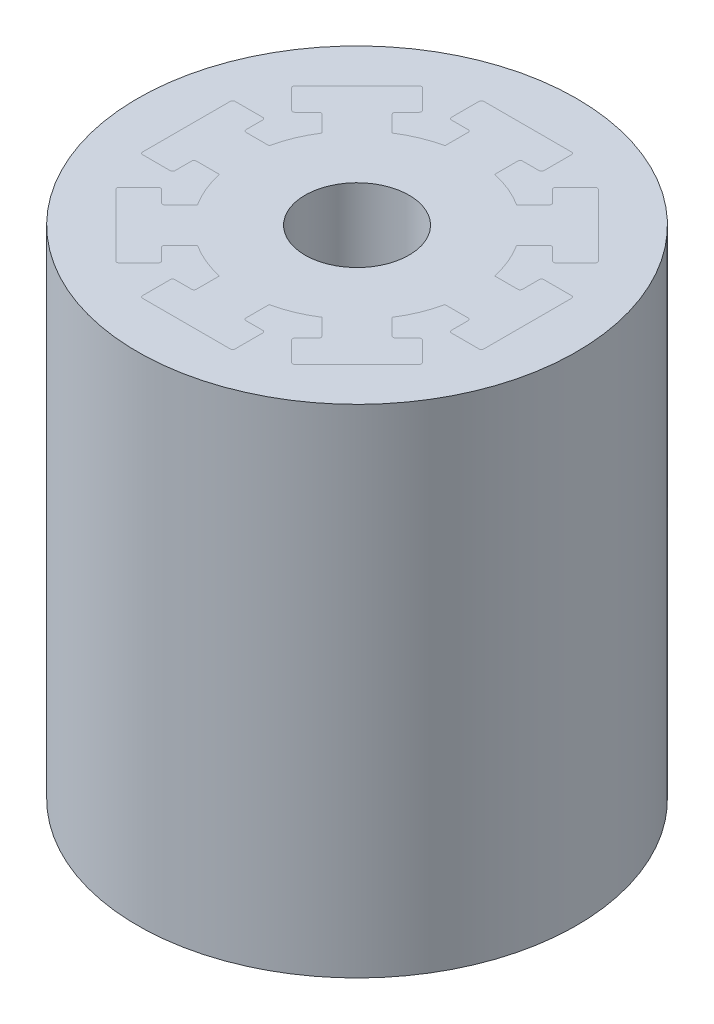
SolidWorks part; units mm, degrees
ref_plane "Front Plane" through (0, 0, 0) normal (0, 0, 1) x (1, 0, 0)
ref_plane "Top Plane" through (0, 0, 0) normal (0, 1, 0) x (1, 0, 0)
ref_plane "Right Plane" through (0, 0, 0) normal (1, 0, 0) x (0, 0, -1)
sketch "Sketch1" plane through (0, 0, 0) normal (0, 1, 0) x (1, 0, 0)
  line L0 (-2.15, 11.7661) -> (-2.15, 9.7661)
  line L1 (-2.35, 11.9661) -> (-3.8, 11.9661)
  line L2 (-4, 12.1661) -> (-4, 14.5661)
  line L3 (-3.8, 14.7661) -> (3.8, 14.7661)
  line L4 (0, 10) -> (0, 14.7661) construction
  line L5 (2.15, 11.7661) -> (2.15, 9.7661)
  line L6 (2.35, 11.9661) -> (3.8, 11.9661)
  line L7 (4, 12.1661) -> (4, 14.5661)
  line L8 (7.7542, 13.1282) -> (13.1282, 7.7542)
  line L9 (11.4312, 5.7743) -> (13.1282, 7.4714)
  line L10 (10.123, 6.7996) -> (11.1483, 5.7743)
  line L11 (9.8402, 6.7996) -> (8.426, 5.3854)
  line L12 (6.7996, 9.8402) -> (5.3854, 8.426)
  line L13 (6.7996, 10.123) -> (5.7743, 11.1483)
  line L14 (5.7743, 11.4312) -> (7.4714, 13.1282)
  line L15 (14.7661, 3.8) -> (14.7661, -3.8)
  line L16 (12.1661, -4) -> (14.5661, -4)
  line L17 (11.9661, -2.35) -> (11.9661, -3.8)
  line L18 (11.7661, -2.15) -> (9.7661, -2.15)
  line L19 (11.7661, 2.15) -> (9.7661, 2.15)
  line L20 (11.9661, 2.35) -> (11.9661, 3.8)
  line L21 (12.1661, 4) -> (14.5661, 4)
  line L22 (13.1282, -7.7542) -> (7.7542, -13.1282)
  line L23 (5.7743, -11.4312) -> (7.4714, -13.1282)
  line L24 (6.7996, -10.123) -> (5.7743, -11.1483)
  line L25 (6.7996, -9.8402) -> (5.3854, -8.426)
  line L26 (9.8402, -6.7996) -> (8.426, -5.3854)
  line L27 (10.123, -6.7996) -> (11.1483, -5.7743)
  line L28 (11.4312, -5.7743) -> (13.1282, -7.4714)
  line L29 (3.8, -14.7661) -> (-3.8, -14.7661)
  line L30 (-4, -12.1661) -> (-4, -14.5661)
  line L31 (-2.35, -11.9661) -> (-3.8, -11.9661)
  line L32 (-2.15, -11.7661) -> (-2.15, -9.7661)
  line L33 (2.15, -11.7661) -> (2.15, -9.7661)
  line L34 (2.35, -11.9661) -> (3.8, -11.9661)
  line L35 (4, -12.1661) -> (4, -14.5661)
  line L36 (-7.7542, -13.1282) -> (-13.1282, -7.7542)
  line L37 (-11.4312, -5.7743) -> (-13.1282, -7.4714)
  line L38 (-10.123, -6.7996) -> (-11.1483, -5.7743)
  line L39 (-9.8402, -6.7996) -> (-8.426, -5.3854)
  line L40 (-6.7996, -9.8402) -> (-5.3854, -8.426)
  line L41 (-6.7996, -10.123) -> (-5.7743, -11.1483)
  line L42 (-5.7743, -11.4312) -> (-7.4714, -13.1282)
  line L43 (-14.7661, -3.8) -> (-14.7661, 3.8)
  line L44 (-12.1661, 4) -> (-14.5661, 4)
  line L45 (-11.9661, 2.35) -> (-11.9661, 3.8)
  line L46 (-11.7661, 2.15) -> (-9.7661, 2.15)
  line L47 (-11.7661, -2.15) -> (-9.7661, -2.15)
  line L48 (-11.9661, -2.35) -> (-11.9661, -3.8)
  line L49 (-12.1661, -4) -> (-14.5661, -4)
  line L50 (-13.1282, 7.7542) -> (-7.7542, 13.1282)
  line L51 (-5.7743, 11.4312) -> (-7.4714, 13.1282)
  line L52 (-6.7996, 10.123) -> (-5.7743, 11.1483)
  line L53 (-6.7996, 9.8402) -> (-5.3854, 8.426)
  line L54 (-9.8402, 6.7996) -> (-8.426, 5.3854)
  line L55 (-10.123, 6.7996) -> (-11.1483, 5.7743)
  line L56 (-11.4312, 5.7743) -> (-13.1282, 7.4714)
  arc A0 (-2.15, 9.7661) -> (-5.3854, 8.426) centre (0, 0) ccw
  arc A1 (-2.15, 11.7661) -> (-2.35, 11.9661) centre (-2.35, 11.7661) ccw
  arc A2 (-3.8, 11.9661) -> (-4, 12.1661) centre (-3.8, 12.1661) cw
  arc A3 (-4, 14.5661) -> (-3.8, 14.7661) centre (-3.8, 14.5661) cw
  arc A4 (2.15, 11.7661) -> (2.35, 11.9661) centre (2.35, 11.7661) cw
  arc A5 (3.8, 11.9661) -> (4, 12.1661) centre (3.8, 12.1661) ccw
  arc A6 (4, 14.5661) -> (3.8, 14.7661) centre (3.8, 14.5661) ccw
  arc A7 (13.1282, 7.4714) -> (13.1282, 7.7542) centre (12.9868, 7.6128) ccw
  arc A8 (11.1483, 5.7743) -> (11.4312, 5.7743) centre (11.2898, 5.9158) ccw
  arc A9 (9.8402, 6.7996) -> (10.123, 6.7996) centre (9.9816, 6.6582) cw
  arc A10 (6.7996, 9.8402) -> (6.7996, 10.123) centre (6.6582, 9.9816) ccw
  arc A11 (5.7743, 11.1483) -> (5.7743, 11.4312) centre (5.9158, 11.2898) cw
  arc A12 (7.4714, 13.1282) -> (7.7542, 13.1282) centre (7.6128, 12.9868) cw
  arc A13 (14.5661, -4) -> (14.7661, -3.8) centre (14.5661, -3.8) ccw
  arc A14 (11.9661, -3.8) -> (12.1661, -4) centre (12.1661, -3.8) ccw
  arc A15 (11.7661, -2.15) -> (11.9661, -2.35) centre (11.7661, -2.35) cw
  arc A16 (11.7661, 2.15) -> (11.9661, 2.35) centre (11.7661, 2.35) ccw
  arc A17 (11.9661, 3.8) -> (12.1661, 4) centre (12.1661, 3.8) cw
  arc A18 (14.5661, 4) -> (14.7661, 3.8) centre (14.5661, 3.8) cw
  arc A19 (7.4714, -13.1282) -> (7.7542, -13.1282) centre (7.6128, -12.9868) ccw
  arc A20 (5.7743, -11.1483) -> (5.7743, -11.4312) centre (5.9158, -11.2898) ccw
  arc A21 (6.7996, -9.8402) -> (6.7996, -10.123) centre (6.6582, -9.9816) cw
  arc A22 (9.8402, -6.7996) -> (10.123, -6.7996) centre (9.9816, -6.6582) ccw
  arc A23 (11.1483, -5.7743) -> (11.4312, -5.7743) centre (11.2898, -5.9158) cw
  arc A24 (13.1282, -7.4714) -> (13.1282, -7.7542) centre (12.9868, -7.6128) cw
  arc A25 (-4, -14.5661) -> (-3.8, -14.7661) centre (-3.8, -14.5661) ccw
  arc A26 (-3.8, -11.9661) -> (-4, -12.1661) centre (-3.8, -12.1661) ccw
  arc A27 (-2.15, -11.7661) -> (-2.35, -11.9661) centre (-2.35, -11.7661) cw
  arc A28 (2.15, -11.7661) -> (2.35, -11.9661) centre (2.35, -11.7661) ccw
  arc A29 (3.8, -11.9661) -> (4, -12.1661) centre (3.8, -12.1661) cw
  arc A30 (4, -14.5661) -> (3.8, -14.7661) centre (3.8, -14.5661) cw
  arc A31 (-13.1282, -7.4714) -> (-13.1282, -7.7542) centre (-12.9868, -7.6128) ccw
  arc A32 (-11.1483, -5.7743) -> (-11.4312, -5.7743) centre (-11.2898, -5.9158) ccw
  arc A33 (-9.8402, -6.7996) -> (-10.123, -6.7996) centre (-9.9816, -6.6582) cw
  arc A34 (-6.7996, -9.8402) -> (-6.7996, -10.123) centre (-6.6582, -9.9816) ccw
  arc A35 (-5.7743, -11.1483) -> (-5.7743, -11.4312) centre (-5.9158, -11.2898) cw
  arc A36 (-7.4714, -13.1282) -> (-7.7542, -13.1282) centre (-7.6128, -12.9868) cw
  arc A37 (-14.5661, 4) -> (-14.7661, 3.8) centre (-14.5661, 3.8) ccw
  arc A38 (-11.9661, 3.8) -> (-12.1661, 4) centre (-12.1661, 3.8) ccw
  arc A39 (-11.7661, 2.15) -> (-11.9661, 2.35) centre (-11.7661, 2.35) cw
  arc A40 (-11.7661, -2.15) -> (-11.9661, -2.35) centre (-11.7661, -2.35) ccw
  arc A41 (-11.9661, -3.8) -> (-12.1661, -4) centre (-12.1661, -3.8) cw
  arc A42 (-14.5661, -4) -> (-14.7661, -3.8) centre (-14.5661, -3.8) cw
  arc A43 (-7.4714, 13.1282) -> (-7.7542, 13.1282) centre (-7.6128, 12.9868) ccw
  arc A44 (-5.7743, 11.1483) -> (-5.7743, 11.4312) centre (-5.9158, 11.2898) ccw
  arc A45 (-6.7996, 9.8402) -> (-6.7996, 10.123) centre (-6.6582, 9.9816) cw
  arc A46 (-9.8402, 6.7996) -> (-10.123, 6.7996) centre (-9.9816, 6.6582) ccw
  arc A47 (-11.1483, 5.7743) -> (-11.4312, 5.7743) centre (-11.2898, 5.9158) cw
  arc A48 (-13.1282, 7.4714) -> (-13.1282, 7.7542) centre (-12.9868, 7.6128) cw
  arc A49 (5.3854, 8.426) -> (2.15, 9.7661) centre (0, 0) ccw
  arc A50 (9.7661, 2.15) -> (8.426, 5.3854) centre (0, 0) ccw
  arc A51 (8.426, -5.3854) -> (9.7661, -2.15) centre (0, 0) ccw
  arc A52 (2.15, -9.7661) -> (5.3854, -8.426) centre (0, 0) ccw
  arc A53 (-5.3854, -8.426) -> (-2.15, -9.7661) centre (0, 0) ccw
  arc A54 (-9.7661, -2.15) -> (-8.426, -5.3854) centre (0, 0) ccw
  arc A55 (-8.426, 5.3854) -> (-9.7661, 2.15) centre (0, 0) ccw
  circle A56 centre (0, 0) radius 4.5
  point P167 (0, 0)
  dimension "D1" = 20
  dimension "D2" = 5
  dimension "D3" = 0.2
  dimension "D5" = 0.2
  dimension "D4" = 0.2
  dimension "D10" = 9
  dimension "D6" = 2.8
  dimension "D7" = 4.3
  dimension "D8" = 8
  dimension "D9" = 8
extrude "Boss-Extrude1" add sketch "Sketch1" along normal blind 43
sketch "Sketch2" plane through (0, 0, 0) normal (0, -1, 0) x (1, 0, 0)
  line L56 (-2.35, -11.9661) -> (-3.8, -11.9661)
  line L57 (-4, -12.1661) -> (-4, -14.5661)
  line L58 (-3.8, -14.7661) -> (3.8, -14.7661)
  line L59 (4, -14.5661) -> (4, -12.1661)
  line L60 (3.8, -11.9661) -> (2.35, -11.9661)
  line L61 (2.15, -11.7661) -> (2.15, -9.7661)
  line L62 (5.3854, -8.426) -> (6.7996, -9.8402)
  line L63 (6.7996, -10.123) -> (5.7743, -11.1483)
  line L64 (5.7743, -11.4312) -> (7.4714, -13.1282)
  line L65 (7.7542, -13.1282) -> (13.1282, -7.7542)
  line L66 (13.1282, -7.4714) -> (11.4312, -5.7743)
  line L67 (11.1483, -5.7743) -> (10.123, -6.7996)
  line L68 (9.8402, -6.7996) -> (8.426, -5.3854)
  line L69 (9.7661, -2.15) -> (11.7661, -2.15)
  line L70 (11.9661, -2.35) -> (11.9661, -3.8)
  line L71 (12.1661, -4) -> (14.5661, -4)
  line L72 (14.7661, -3.8) -> (14.7661, 3.8)
  line L73 (14.5661, 4) -> (12.1661, 4)
  line L74 (11.9661, 3.8) -> (11.9661, 2.35)
  line L75 (11.7661, 2.15) -> (9.7661, 2.15)
  line L76 (8.426, 5.3854) -> (9.8402, 6.7996)
  line L77 (10.123, 6.7996) -> (11.1483, 5.7743)
  line L78 (11.4312, 5.7743) -> (13.1282, 7.4714)
  line L79 (13.1282, 7.7542) -> (7.7542, 13.1282)
  line L80 (7.4714, 13.1282) -> (5.7743, 11.4312)
  line L81 (5.7743, 11.1483) -> (6.7996, 10.123)
  line L82 (6.7996, 9.8402) -> (5.3854, 8.426)
  line L83 (2.15, 9.7661) -> (2.15, 11.7661)
  line L84 (2.35, 11.9661) -> (3.8, 11.9661)
  line L85 (4, 12.1661) -> (4, 14.5661)
  line L86 (3.8, 14.7661) -> (-3.8, 14.7661)
  line L87 (-4, 14.5661) -> (-4, 12.1661)
  line L88 (-3.8, 11.9661) -> (-2.35, 11.9661)
  line L89 (-2.15, 11.7661) -> (-2.15, 9.7661)
  line L90 (-5.3854, 8.426) -> (-6.7996, 9.8402)
  line L91 (-6.7996, 10.123) -> (-5.7743, 11.1483)
  line L92 (-5.7743, 11.4312) -> (-7.4714, 13.1282)
  line L93 (-7.7542, 13.1282) -> (-13.1282, 7.7542)
  line L94 (-13.1282, 7.4714) -> (-11.4312, 5.7743)
  line L95 (-11.1483, 5.7743) -> (-10.123, 6.7996)
  line L96 (-9.8402, 6.7996) -> (-8.426, 5.3854)
  line L97 (-9.7661, 2.15) -> (-11.7661, 2.15)
  line L98 (-11.9661, 2.35) -> (-11.9661, 3.8)
  line L99 (-12.1661, 4) -> (-14.5661, 4)
  line L100 (-14.7661, 3.8) -> (-14.7661, -3.8)
  line L101 (-14.5661, -4) -> (-12.1661, -4)
  line L102 (-11.9661, -3.8) -> (-11.9661, -2.35)
  line L103 (-11.7661, -2.15) -> (-9.7661, -2.15)
  line L104 (-8.426, -5.3854) -> (-9.8402, -6.7996)
  line L105 (-10.123, -6.7996) -> (-11.1483, -5.7743)
  line L106 (-11.4312, -5.7743) -> (-13.1282, -7.4714)
  line L107 (-13.1282, -7.7542) -> (-7.7542, -13.1282)
  line L108 (-7.4714, -13.1282) -> (-5.7743, -11.4312)
  line L109 (-5.7743, -11.1483) -> (-6.7996, -10.123)
  line L110 (-6.7996, -9.8402) -> (-5.3854, -8.426)
  line L111 (-2.15, -9.7661) -> (-2.15, -11.7661)
  line L112 (-2.35, -11.9661) -> (-3.8, -11.9661)
  line L113 (-4, -12.1661) -> (-4, -14.5661)
  line L114 (-3.8, -14.7661) -> (3.8, -14.7661)
  line L115 (4, -14.5661) -> (4, -12.1661)
  line L116 (3.8, -11.9661) -> (2.35, -11.9661)
  line L117 (2.15, -11.7661) -> (2.15, -9.7661)
  line L118 (5.3854, -8.426) -> (6.7996, -9.8402)
  line L119 (6.7996, -10.123) -> (5.7743, -11.1483)
  line L120 (5.7743, -11.4312) -> (7.4714, -13.1282)
  line L121 (7.7542, -13.1282) -> (13.1282, -7.7542)
  line L122 (13.1282, -7.4714) -> (11.4312, -5.7743)
  line L123 (11.1483, -5.7743) -> (10.123, -6.7996)
  line L124 (9.8402, -6.7996) -> (8.426, -5.3854)
  line L125 (9.7661, -2.15) -> (11.7661, -2.15)
  line L126 (11.9661, -2.35) -> (11.9661, -3.8)
  line L127 (12.1661, -4) -> (14.5661, -4)
  line L128 (14.7661, -3.8) -> (14.7661, 3.8)
  line L129 (14.5661, 4) -> (12.1661, 4)
  line L130 (11.9661, 3.8) -> (11.9661, 2.35)
  line L131 (11.7661, 2.15) -> (9.7661, 2.15)
  line L132 (8.426, 5.3854) -> (9.8402, 6.7996)
  line L133 (10.123, 6.7996) -> (11.1483, 5.7743)
  line L134 (11.4312, 5.7743) -> (13.1282, 7.4714)
  line L135 (13.1282, 7.7542) -> (7.7542, 13.1282)
  line L136 (7.4714, 13.1282) -> (5.7743, 11.4312)
  line L137 (5.7743, 11.1483) -> (6.7996, 10.123)
  line L138 (6.7996, 9.8402) -> (5.3854, 8.426)
  line L139 (2.15, 9.7661) -> (2.15, 11.7661)
  line L140 (2.35, 11.9661) -> (3.8, 11.9661)
  line L141 (4, 12.1661) -> (4, 14.5661)
  line L142 (3.8, 14.7661) -> (-3.8, 14.7661)
  line L143 (-4, 14.5661) -> (-4, 12.1661)
  line L144 (-3.8, 11.9661) -> (-2.35, 11.9661)
  line L145 (-2.15, 11.7661) -> (-2.15, 9.7661)
  line L146 (-5.3854, 8.426) -> (-6.7996, 9.8402)
  line L147 (-6.7996, 10.123) -> (-5.7743, 11.1483)
  line L148 (-5.7743, 11.4312) -> (-7.4714, 13.1282)
  line L149 (-7.7542, 13.1282) -> (-13.1282, 7.7542)
  line L150 (-13.1282, 7.4714) -> (-11.4312, 5.7743)
  line L151 (-11.1483, 5.7743) -> (-10.123, 6.7996)
  line L152 (-9.8402, 6.7996) -> (-8.426, 5.3854)
  line L153 (-9.7661, 2.15) -> (-11.7661, 2.15)
  line L154 (-11.9661, 2.35) -> (-11.9661, 3.8)
  line L155 (-12.1661, 4) -> (-14.5661, 4)
  line L156 (-14.7661, 3.8) -> (-14.7661, -3.8)
  line L157 (-14.5661, -4) -> (-12.1661, -4)
  line L158 (-11.9661, -3.8) -> (-11.9661, -2.35)
  line L159 (-11.7661, -2.15) -> (-9.7661, -2.15)
  line L160 (-8.426, -5.3854) -> (-9.8402, -6.7996)
  line L161 (-10.123, -6.7996) -> (-11.1483, -5.7743)
  line L162 (-11.4312, -5.7743) -> (-13.1282, -7.4714)
  line L163 (-13.1282, -7.7542) -> (-7.7542, -13.1282)
  line L164 (-7.4714, -13.1282) -> (-5.7743, -11.4312)
  line L165 (-5.7743, -11.1483) -> (-6.7996, -10.123)
  line L166 (-6.7996, -9.8402) -> (-5.3854, -8.426)
  line L167 (-2.15, -9.7661) -> (-2.15, -11.7661)
  circle A1 centre (0, 0) radius 19
  arc A57 (-2.35, -11.9661) -> (-2.15, -11.7661) centre (-2.35, -11.7661) ccw
  arc A58 (-3.8, -11.9661) -> (-4, -12.1661) centre (-3.8, -12.1661) ccw
  arc A59 (-4, -14.5661) -> (-3.8, -14.7661) centre (-3.8, -14.5661) ccw
  arc A60 (3.8, -14.7661) -> (4, -14.5661) centre (3.8, -14.5661) ccw
  arc A61 (4, -12.1661) -> (3.8, -11.9661) centre (3.8, -12.1661) ccw
  arc A62 (2.15, -11.7661) -> (2.35, -11.9661) centre (2.35, -11.7661) ccw
  arc A63 (2.15, -9.7661) -> (5.3854, -8.426) centre (0, 0) ccw
  arc A64 (6.7996, -10.123) -> (6.7996, -9.8402) centre (6.6582, -9.9816) ccw
  arc A65 (5.7743, -11.1483) -> (5.7743, -11.4312) centre (5.9158, -11.2898) ccw
  arc A66 (7.4714, -13.1282) -> (7.7542, -13.1282) centre (7.6128, -12.9868) ccw
  arc A67 (13.1282, -7.7542) -> (13.1282, -7.4714) centre (12.9868, -7.6128) ccw
  arc A68 (11.4312, -5.7743) -> (11.1483, -5.7743) centre (11.2898, -5.9158) ccw
  arc A69 (9.8402, -6.7996) -> (10.123, -6.7996) centre (9.9816, -6.6582) ccw
  arc A70 (8.426, -5.3854) -> (9.7661, -2.15) centre (0, 0) ccw
  arc A71 (11.9661, -2.35) -> (11.7661, -2.15) centre (11.7661, -2.35) ccw
  arc A72 (11.9661, -3.8) -> (12.1661, -4) centre (12.1661, -3.8) ccw
  arc A73 (14.5661, -4) -> (14.7661, -3.8) centre (14.5661, -3.8) ccw
  arc A74 (14.7661, 3.8) -> (14.5661, 4) centre (14.5661, 3.8) ccw
  arc A75 (12.1661, 4) -> (11.9661, 3.8) centre (12.1661, 3.8) ccw
  arc A76 (11.7661, 2.15) -> (11.9661, 2.35) centre (11.7661, 2.35) ccw
  arc A77 (9.7661, 2.15) -> (8.426, 5.3854) centre (0, 0) ccw
  arc A78 (10.123, 6.7996) -> (9.8402, 6.7996) centre (9.9816, 6.6582) ccw
  arc A79 (11.1483, 5.7743) -> (11.4312, 5.7743) centre (11.2898, 5.9158) ccw
  arc A80 (13.1282, 7.4714) -> (13.1282, 7.7542) centre (12.9868, 7.6128) ccw
  arc A81 (7.7542, 13.1282) -> (7.4714, 13.1282) centre (7.6128, 12.9868) ccw
  arc A82 (5.7743, 11.4312) -> (5.7743, 11.1483) centre (5.9158, 11.2898) ccw
  arc A83 (6.7996, 9.8402) -> (6.7996, 10.123) centre (6.6582, 9.9816) ccw
  arc A84 (5.3854, 8.426) -> (2.15, 9.7661) centre (0, 0) ccw
  arc A85 (2.35, 11.9661) -> (2.15, 11.7661) centre (2.35, 11.7661) ccw
  arc A86 (3.8, 11.9661) -> (4, 12.1661) centre (3.8, 12.1661) ccw
  arc A87 (4, 14.5661) -> (3.8, 14.7661) centre (3.8, 14.5661) ccw
  arc A88 (-3.8, 14.7661) -> (-4, 14.5661) centre (-3.8, 14.5661) ccw
  arc A89 (-4, 12.1661) -> (-3.8, 11.9661) centre (-3.8, 12.1661) ccw
  arc A90 (-2.15, 11.7661) -> (-2.35, 11.9661) centre (-2.35, 11.7661) ccw
  arc A91 (-2.15, 9.7661) -> (-5.3854, 8.426) centre (0, 0) ccw
  arc A92 (-6.7996, 10.123) -> (-6.7996, 9.8402) centre (-6.6582, 9.9816) ccw
  arc A93 (-5.7743, 11.1483) -> (-5.7743, 11.4312) centre (-5.9158, 11.2898) ccw
  arc A94 (-7.4714, 13.1282) -> (-7.7542, 13.1282) centre (-7.6128, 12.9868) ccw
  arc A95 (-13.1282, 7.7542) -> (-13.1282, 7.4714) centre (-12.9868, 7.6128) ccw
  arc A96 (-11.4312, 5.7743) -> (-11.1483, 5.7743) centre (-11.2898, 5.9158) ccw
  arc A97 (-9.8402, 6.7996) -> (-10.123, 6.7996) centre (-9.9816, 6.6582) ccw
  arc A98 (-8.426, 5.3854) -> (-9.7661, 2.15) centre (0, 0) ccw
  arc A99 (-11.9661, 2.35) -> (-11.7661, 2.15) centre (-11.7661, 2.35) ccw
  arc A100 (-11.9661, 3.8) -> (-12.1661, 4) centre (-12.1661, 3.8) ccw
  arc A101 (-14.5661, 4) -> (-14.7661, 3.8) centre (-14.5661, 3.8) ccw
  arc A102 (-14.7661, -3.8) -> (-14.5661, -4) centre (-14.5661, -3.8) ccw
  arc A103 (-12.1661, -4) -> (-11.9661, -3.8) centre (-12.1661, -3.8) ccw
  arc A104 (-11.7661, -2.15) -> (-11.9661, -2.35) centre (-11.7661, -2.35) ccw
  arc A105 (-9.7661, -2.15) -> (-8.426, -5.3854) centre (0, 0) ccw
  arc A106 (-10.123, -6.7996) -> (-9.8402, -6.7996) centre (-9.9816, -6.6582) ccw
  arc A107 (-11.1483, -5.7743) -> (-11.4312, -5.7743) centre (-11.2898, -5.9158) ccw
  arc A108 (-13.1282, -7.4714) -> (-13.1282, -7.7542) centre (-12.9868, -7.6128) ccw
  arc A109 (-7.7542, -13.1282) -> (-7.4714, -13.1282) centre (-7.6128, -12.9868) ccw
  arc A110 (-5.7743, -11.4312) -> (-5.7743, -11.1483) centre (-5.9158, -11.2898) ccw
  arc A111 (-6.7996, -9.8402) -> (-6.7996, -10.123) centre (-6.6582, -9.9816) ccw
  arc A112 (-5.3854, -8.426) -> (-2.15, -9.7661) centre (0, 0) ccw
  arc A113 (-2.35, -11.9661) -> (-2.15, -11.7661) centre (-2.35, -11.7661) ccw
  arc A114 (-3.8, -11.9661) -> (-4, -12.1661) centre (-3.8, -12.1661) ccw
  arc A115 (-4, -14.5661) -> (-3.8, -14.7661) centre (-3.8, -14.5661) ccw
  arc A116 (3.8, -14.7661) -> (4, -14.5661) centre (3.8, -14.5661) ccw
  arc A117 (4, -12.1661) -> (3.8, -11.9661) centre (3.8, -12.1661) ccw
  arc A118 (2.15, -11.7661) -> (2.35, -11.9661) centre (2.35, -11.7661) ccw
  arc A119 (2.15, -9.7661) -> (5.3854, -8.426) centre (0, 0) ccw
  arc A120 (6.7996, -10.123) -> (6.7996, -9.8402) centre (6.6582, -9.9816) ccw
  arc A121 (5.7743, -11.1483) -> (5.7743, -11.4312) centre (5.9158, -11.2898) ccw
  arc A122 (7.4714, -13.1282) -> (7.7542, -13.1282) centre (7.6128, -12.9868) ccw
  arc A123 (13.1282, -7.7542) -> (13.1282, -7.4714) centre (12.9868, -7.6128) ccw
  arc A124 (11.4312, -5.7743) -> (11.1483, -5.7743) centre (11.2898, -5.9158) ccw
  arc A125 (9.8402, -6.7996) -> (10.123, -6.7996) centre (9.9816, -6.6582) ccw
  arc A126 (8.426, -5.3854) -> (9.7661, -2.15) centre (0, 0) ccw
  arc A127 (11.9661, -2.35) -> (11.7661, -2.15) centre (11.7661, -2.35) ccw
  arc A128 (11.9661, -3.8) -> (12.1661, -4) centre (12.1661, -3.8) ccw
  arc A129 (14.5661, -4) -> (14.7661, -3.8) centre (14.5661, -3.8) ccw
  arc A130 (14.7661, 3.8) -> (14.5661, 4) centre (14.5661, 3.8) ccw
  arc A131 (12.1661, 4) -> (11.9661, 3.8) centre (12.1661, 3.8) ccw
  arc A132 (11.7661, 2.15) -> (11.9661, 2.35) centre (11.7661, 2.35) ccw
  arc A133 (9.7661, 2.15) -> (8.426, 5.3854) centre (0, 0) ccw
  arc A134 (10.123, 6.7996) -> (9.8402, 6.7996) centre (9.9816, 6.6582) ccw
  arc A135 (11.1483, 5.7743) -> (11.4312, 5.7743) centre (11.2898, 5.9158) ccw
  arc A136 (13.1282, 7.4714) -> (13.1282, 7.7542) centre (12.9868, 7.6128) ccw
  arc A137 (7.7542, 13.1282) -> (7.4714, 13.1282) centre (7.6128, 12.9868) ccw
  arc A138 (5.7743, 11.4312) -> (5.7743, 11.1483) centre (5.9158, 11.2898) ccw
  arc A139 (6.7996, 9.8402) -> (6.7996, 10.123) centre (6.6582, 9.9816) ccw
  arc A140 (5.3854, 8.426) -> (2.15, 9.7661) centre (0, 0) ccw
  arc A141 (2.35, 11.9661) -> (2.15, 11.7661) centre (2.35, 11.7661) ccw
  arc A142 (3.8, 11.9661) -> (4, 12.1661) centre (3.8, 12.1661) ccw
  arc A143 (4, 14.5661) -> (3.8, 14.7661) centre (3.8, 14.5661) ccw
  arc A144 (-3.8, 14.7661) -> (-4, 14.5661) centre (-3.8, 14.5661) ccw
  arc A145 (-4, 12.1661) -> (-3.8, 11.9661) centre (-3.8, 12.1661) ccw
  arc A146 (-2.15, 11.7661) -> (-2.35, 11.9661) centre (-2.35, 11.7661) ccw
  arc A147 (-2.15, 9.7661) -> (-5.3854, 8.426) centre (0, 0) ccw
  arc A148 (-6.7996, 10.123) -> (-6.7996, 9.8402) centre (-6.6582, 9.9816) ccw
  arc A149 (-5.7743, 11.1483) -> (-5.7743, 11.4312) centre (-5.9158, 11.2898) ccw
  arc A150 (-7.4714, 13.1282) -> (-7.7542, 13.1282) centre (-7.6128, 12.9868) ccw
  arc A151 (-13.1282, 7.7542) -> (-13.1282, 7.4714) centre (-12.9868, 7.6128) ccw
  arc A152 (-11.4312, 5.7743) -> (-11.1483, 5.7743) centre (-11.2898, 5.9158) ccw
  arc A153 (-9.8402, 6.7996) -> (-10.123, 6.7996) centre (-9.9816, 6.6582) ccw
  arc A154 (-8.426, 5.3854) -> (-9.7661, 2.15) centre (0, 0) ccw
  arc A155 (-11.9661, 2.35) -> (-11.7661, 2.15) centre (-11.7661, 2.35) ccw
  arc A156 (-11.9661, 3.8) -> (-12.1661, 4) centre (-12.1661, 3.8) ccw
  arc A157 (-14.5661, 4) -> (-14.7661, 3.8) centre (-14.5661, 3.8) ccw
  arc A158 (-14.7661, -3.8) -> (-14.5661, -4) centre (-14.5661, -3.8) ccw
  arc A159 (-12.1661, -4) -> (-11.9661, -3.8) centre (-12.1661, -3.8) ccw
  arc A160 (-11.7661, -2.15) -> (-11.9661, -2.35) centre (-11.7661, -2.35) ccw
  arc A161 (-9.7661, -2.15) -> (-8.426, -5.3854) centre (0, 0) ccw
  arc A162 (-10.123, -6.7996) -> (-9.8402, -6.7996) centre (-9.9816, -6.6582) ccw
  arc A163 (-11.1483, -5.7743) -> (-11.4312, -5.7743) centre (-11.2898, -5.9158) ccw
  arc A164 (-13.1282, -7.4714) -> (-13.1282, -7.7542) centre (-12.9868, -7.6128) ccw
  arc A165 (-7.7542, -13.1282) -> (-7.4714, -13.1282) centre (-7.6128, -12.9868) ccw
  arc A166 (-5.7743, -11.4312) -> (-5.7743, -11.1483) centre (-5.9158, -11.2898) ccw
  arc A167 (-6.7996, -9.8402) -> (-6.7996, -10.123) centre (-6.6582, -9.9816) ccw
  arc A168 (-5.3854, -8.426) -> (-2.15, -9.7661) centre (0, 0) ccw
  dimension "D1" = 0
  dimension "D2" = 38
extrude "Boss-Extrude2" add sketch "Sketch2" against normal up to vertex (43 mm away) separate body
